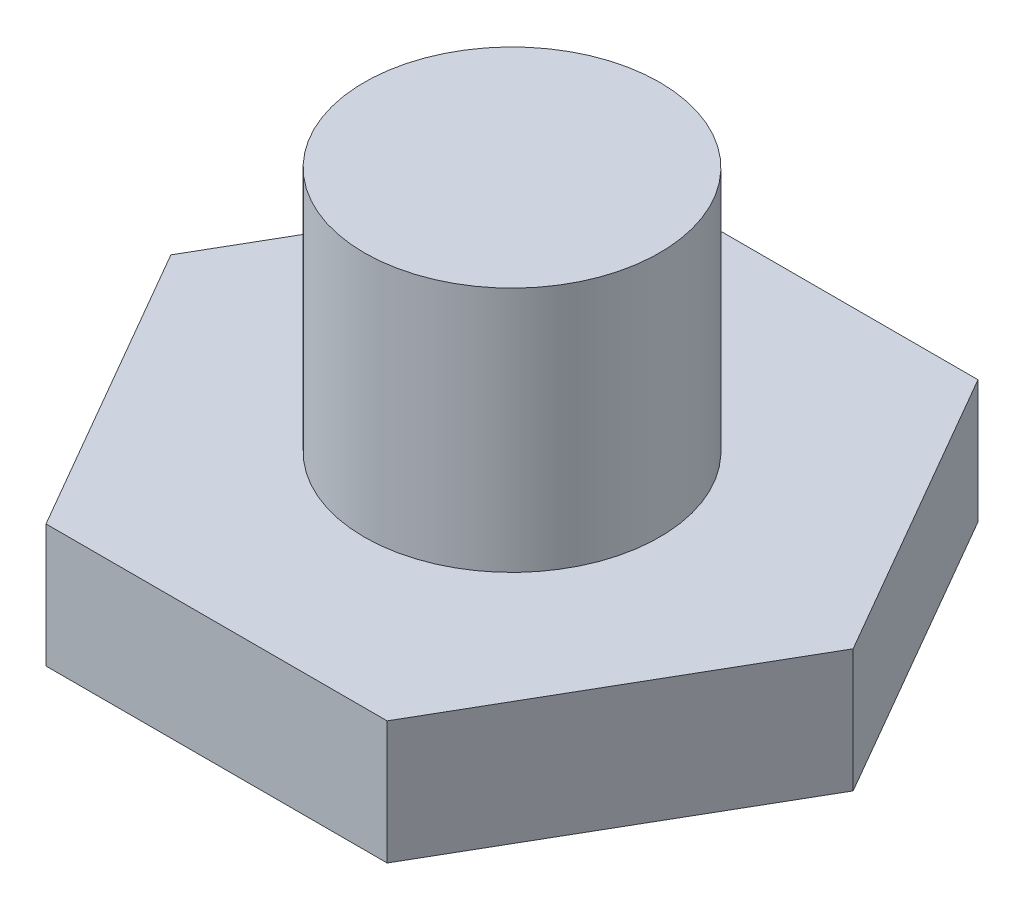
SolidWorks part; units mm, degrees
material "Сталь 3 ГОСТ 535-88"
ref_plane "Спереди" through (0, 0, 0) normal (0, 0, 1) x (1, 0, 0)
ref_plane "Сверху" through (0, 0, 0) normal (0, 1, 0) x (1, 0, 0)
ref_plane "Справа" through (0, 0, 0) normal (1, 0, 0) x (0, 0, -1)
sketch "Эскиз1" plane through (0, 0, 0) normal (0, 1, 0) x (1, 0, 0)
  line L1 (13.8564, 0) -> (6.9282, 12)
  line L2 (6.9282, 12) -> (-6.9282, 12)
  line L3 (-6.9282, 12) -> (-13.8564, 0)
  line L4 (-13.8564, 0) -> (-6.9282, -12)
  line L5 (-6.9282, -12) -> (6.9282, -12)
  line L6 (6.9282, -12) -> (13.8564, 0)
  circle A0 centre (0, 0) radius 12 construction
  dimension "D1" = 24
extrude "Бобышка-Вытянуть1" add sketch "Эскиз1" along normal blind 15
sketch "Эскиз2" plane through (0, 15, 0) normal (0, 1, 0) x (1, 0, 0)
  circle A0 centre (0, 0) radius 6
  dimension "D1" = 12
extrude "Вырез-Вытянуть1" cut sketch "Эскиз2" against normal offset from surface (10 mm away) 5 flip side to cut up to face at (0, 0, 0)
cosmetic thread "Условное изображение резьбы1" parameters "D2"=10.072
